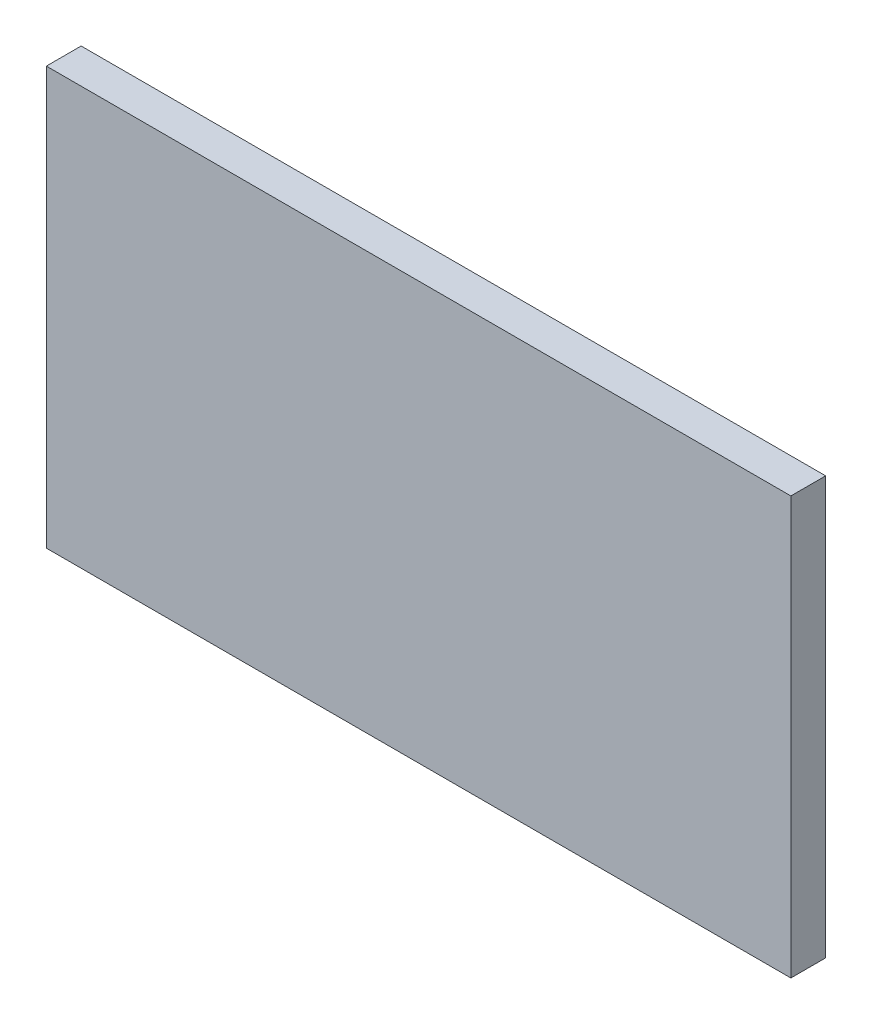
SolidWorks part; units mm, degrees
ref_plane "前视基准面" through (0, 0, 0) normal (0, 0, 1) x (1, 0, 0)
ref_plane "上视基准面" through (0, 0, 0) normal (0, 1, 0) x (1, 0, 0)
ref_plane "右视基准面" through (0, 0, 0) normal (1, 0, 0) x (0, 0, -1)
sketch "草图1" plane through (0, 0, 0) normal (0, 0, 1) x (1, 0, 0)
  line L1 (107, -60) -> (-107, -60)
  line L2 (107, -60) -> (107, 60)
  line L3 (107, 60) -> (-107, 60)
  line L4 (-107, -60) -> (-107, 60)
  line L5 (107, -60) -> (-107, 60) construction
  line L6 (107, 60) -> (-107, -60) construction
  point P0 (0, 0)
  dimension "D1" = 214
  dimension "D2" = 120
extrude "凸台-拉伸1" add sketch "草图1" along normal blind 10
